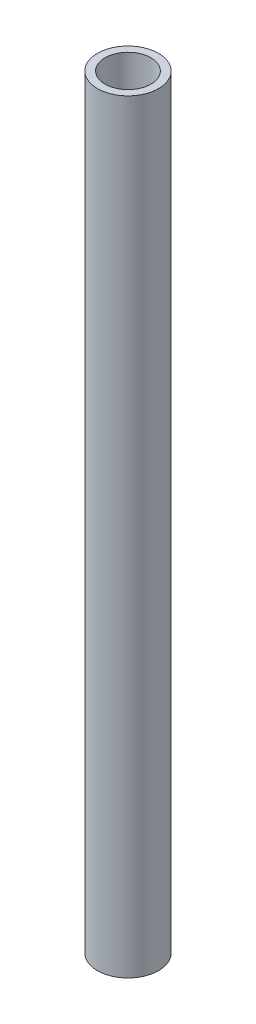
SolidWorks part; units mm, degrees
ref_plane "Front Plane" through (0, 0, 0) normal (0, 0, 1) x (1, 0, 0)
ref_plane "Top Plane" through (0, 0, 0) normal (0, 1, 0) x (1, 0, 0)
ref_plane "Right Plane" through (0, 0, 0) normal (1, 0, 0) x (0, 0, -1)
sketch "Sketch1" plane through (0, 0, 0) normal (0, 1, 0) x (1, 0, 0)
  circle A0 centre (0, 0) radius 4
  circle A1 centre (0, 0) radius 3
  dimension "D1" = 8
  dimension "D2" = 6
extrude "Boss-Extrude1" add sketch "Sketch1" along normal blind 100
